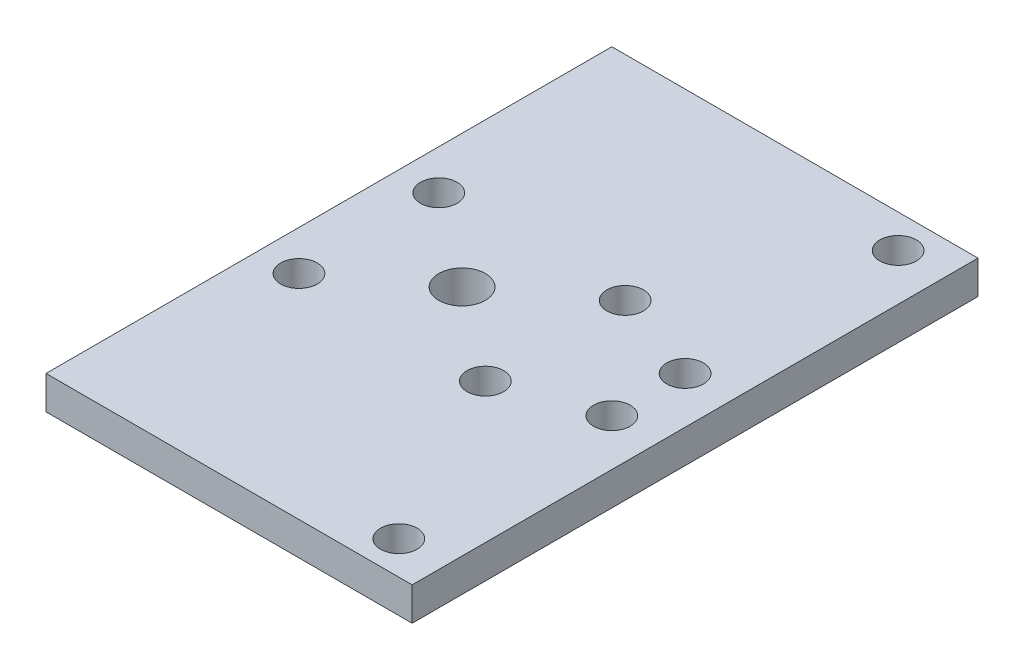
SolidWorks part; units mm, degrees
ref_plane "Front Plane" through (0, 0, 0) normal (0, 0, 1) x (1, 0, 0)
ref_plane "Top Plane" through (0, 0, 0) normal (0, 1, 0) x (1, 0, 0)
ref_plane "Right Plane" through (0, 0, 0) normal (1, 0, 0) x (0, 0, -1)
ref_plane "Plane1" through (0, 0, 0) normal (0, -1, 0) x (1, 0, 0)
sketch "Sketch1" plane through (0, 0, 0) normal (0, -1, 0) x (1, 0, 0)
  line L0 (-20, -42.5) -> (35, -42.5)
  line L1 (35, -42.5) -> (35, 42.5)
  line L2 (35, 42.5) -> (-20, 42.5)
  line L3 (-20, 42.5) -> (-20, -42.5)
  circle A0 centre (14, 10.5) radius 2.75
  circle A1 centre (-14, 10.5) radius 2.75
  circle A2 centre (-14, -10.5) radius 2.75
  circle A3 centre (14, -10.5) radius 2.75
  circle A4 centre (28, 37.5) radius 2.75
  circle A5 centre (28, 5.5) radius 2.75
  circle A6 centre (28, -5.5) radius 2.75
  circle A7 centre (28, -37.5) radius 2.75
  circle A8 centre (0, 0) radius 3.5
extrude "Boss-Extrude1" add sketch "Sketch1" against normal blind 5
